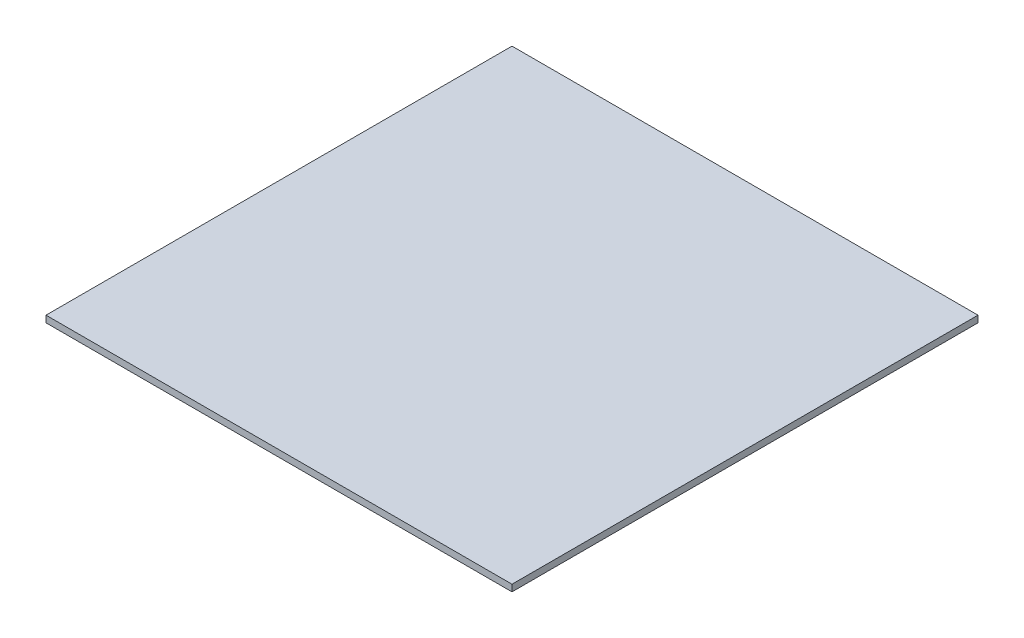
SolidWorks part; units mm, degrees
material "Epoxy, Unfilled"
ref_plane "Front Plane" through (0, 0, 0) normal (0, 0, 1) x (1, 0, 0)
ref_plane "Top Plane" through (0, 0, 0) normal (0, 1, 0) x (1, 0, 0)
ref_plane "Right Plane" through (0, 0, 0) normal (1, 0, 0) x (0, 0, -1)
sketch "Sketch1" plane through (0, 0, 0) normal (0, 1, 0) x (1, 0, 0)
  line L1 (-17.78, -17.78) -> (17.78, -17.78)
  line L2 (-17.78, -17.78) -> (-17.78, 17.78)
  line L3 (-17.78, 17.78) -> (17.78, 17.78)
  line L4 (17.78, -17.78) -> (17.78, 17.78)
  line L5 (-17.78, -17.78) -> (17.78, 17.78) construction
  line L6 (-17.78, 17.78) -> (17.78, -17.78) construction
  point P0 (0, 0)
  dimension "D1" = 35.56
  dimension "D2" = 35.56
extrude "Boss-Extrude1" add sketch "Sketch1" along normal mid plane 0.508
